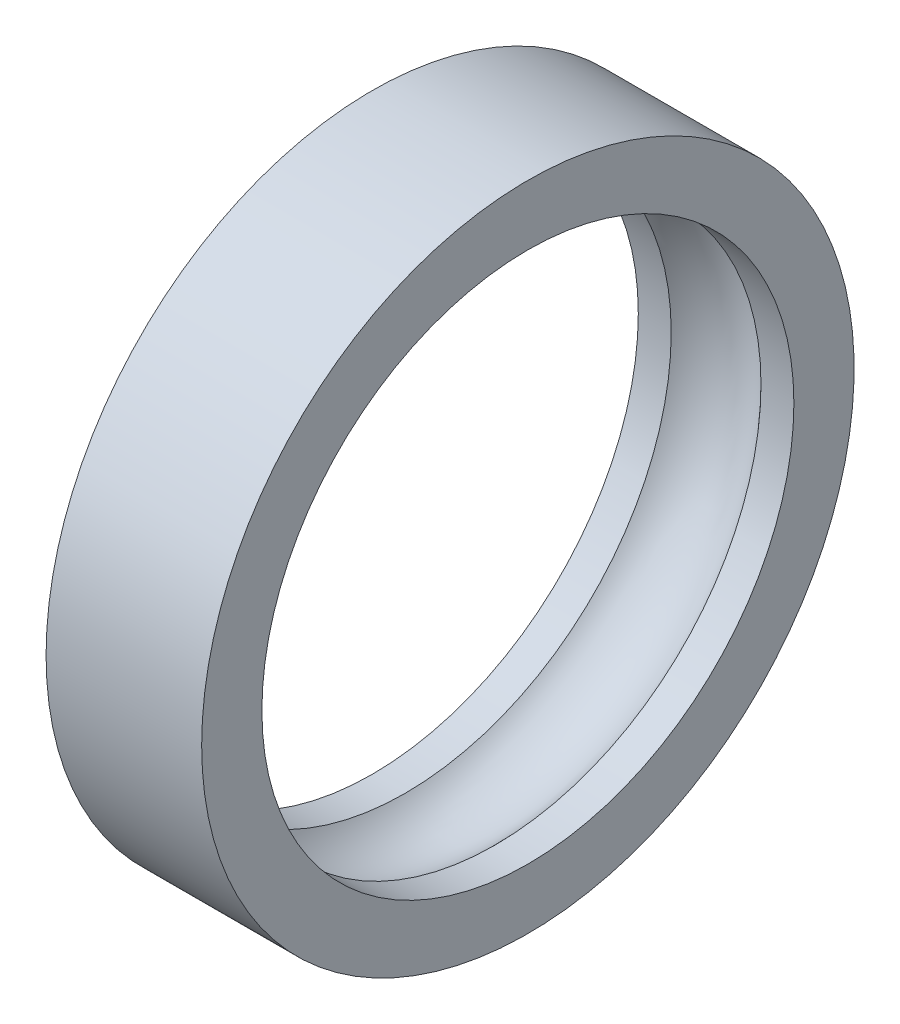
SolidWorks part; units mm, degrees
ref_plane "Front Plane" through (0, 0, 0) normal (0, 0, 1) x (1, 0, 0)
ref_plane "Top Plane" through (0, 0, 0) normal (0, 1, 0) x (1, 0, 0)
ref_plane "Right Plane" through (0, 0, 0) normal (1, 0, 0) x (0, 0, -1)
sketch "Sketch1" plane through (0, 0, 0) normal (0, 0, 1) x (1, 0, 0)
  line L0 (0, 0) -> (0, 61.4139) construction
  line L1 (-15.5, 65) -> (15.5, 65)
  line L2 (-15.5, 65) -> (-15.5, 53)
  line L3 (-15.5, 53) -> (-8.9443, 53)
  line L4 (15.5, 65) -> (15.5, 53)
  line L5 (8.9443, 53) -> (15.5, 53)
  line L6 (0, 0) -> (70.4901, 0) construction
  arc A1 (-8.9443, 53) -> (8.9443, 53) centre (0, 45) cw
  dimension "D5" = 12
  dimension "D1" = 31
  dimension "D2" = 53
  dimension "D3" = 65
  dimension "D4" = 15.5
  dimension "D6" = 8
revolve "Revolve1" add sketch "Sketch1" angle 360 about L6
